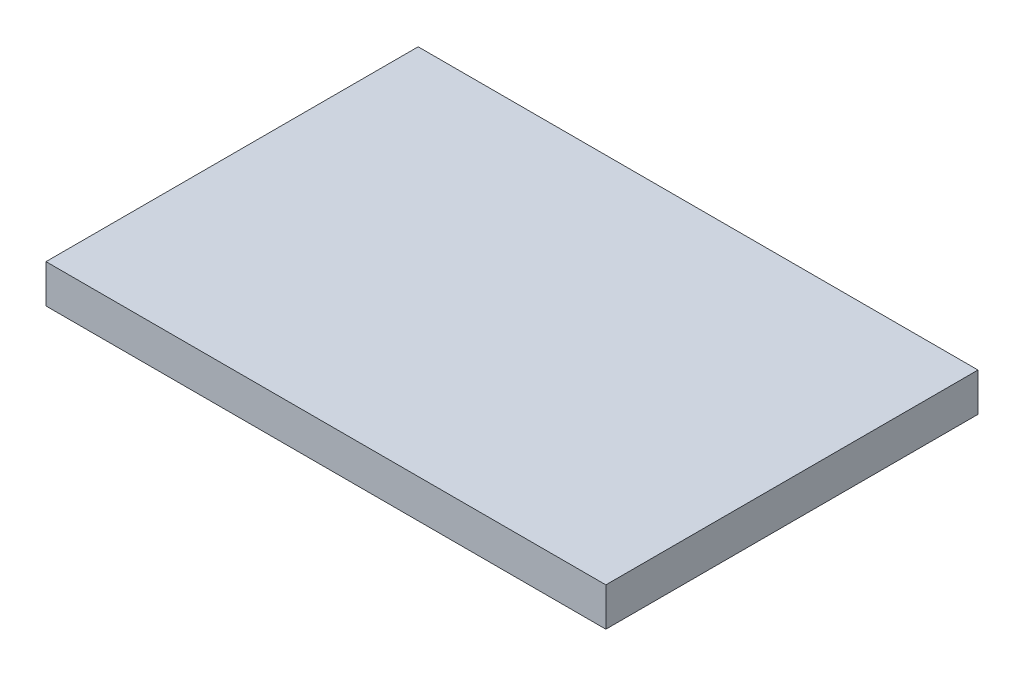
SolidWorks part; units mm, degrees
material "PLA"
ref_plane "Front Plane" through (0, 0, 0) normal (0, 0, 1) x (1, 0, 0)
ref_plane "Top Plane" through (0, 0, 0) normal (0, 1, 0) x (1, 0, 0)
ref_plane "Right Plane" through (0, 0, 0) normal (1, 0, 0) x (0, 0, -1)
sketch "Sketch1" plane through (0, 0, 0) normal (0, 1, 0) x (1, 0, 0)
  line L1 (-25.5, -16.95) -> (25.5, -16.95)
  line L2 (-25.5, -16.95) -> (-25.5, 16.95)
  line L3 (-25.5, 16.95) -> (25.5, 16.95)
  line L4 (25.5, -16.95) -> (25.5, 16.95)
  point P4 (0, 16.95)
  point P6 (25.5, 0)
  dimension "D1" = 51
  dimension "D2" = 33.9
extrude "Boss-Extrude1" add sketch "Sketch1" along normal blind 3.5
